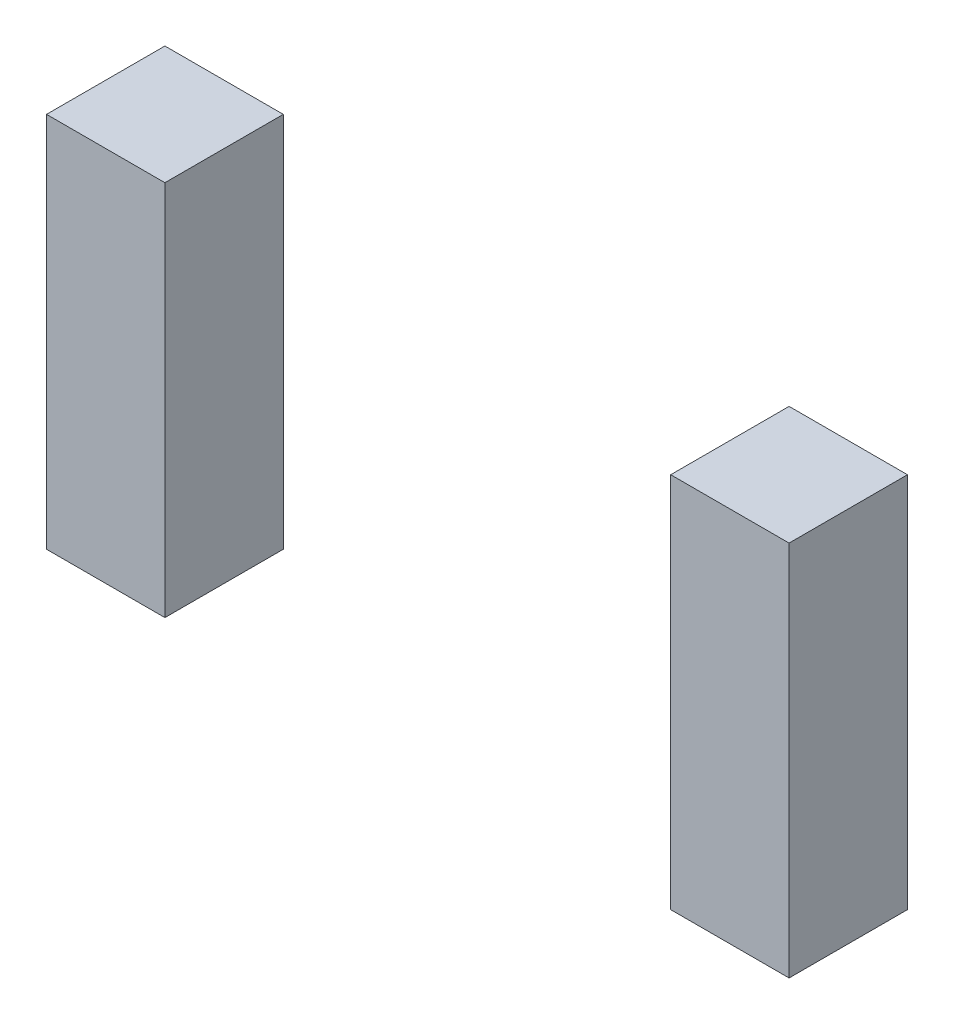
SolidWorks part; units mm, degrees
ref_plane "Plan de face" through (0, 0, 0) normal (0, 0, 1) x (1, 0, 0)
ref_plane "Plan de dessus" through (0, 0, 0) normal (0, 1, 0) x (1, 0, 0)
ref_plane "Plan de droite" through (0, 0, 0) normal (1, 0, 0) x (0, 0, -1)
sketch "Esquisse1" plane through (0, 0, 0) normal (0, 1, 0) x (1, 0, 0)
  line L1 (-50.5177, 16.6424) -> (-28.5177, 16.6424)
  line L2 (-50.5177, 16.6424) -> (-50.5177, -5.3576)
  line L3 (-50.5177, -5.3576) -> (-28.5177, -5.3576)
  line L4 (-28.5177, 16.6424) -> (-28.5177, -5.3576)
  line L5 (65.4823, 16.6424) -> (87.4823, 16.6424)
  line L6 (65.4823, 16.6424) -> (65.4823, -5.3576)
  line L7 (65.4823, -5.3576) -> (87.4823, -5.3576)
  line L8 (87.4823, 16.6424) -> (87.4823, -5.3576)
  dimension "D1" = 22
  dimension "D2" = 22
  dimension "D3" = 22
  dimension "D4" = 22
  dimension "D5" = 94
extrude "Boss.-Extru.1" add sketch "Esquisse1" along normal blind 70
